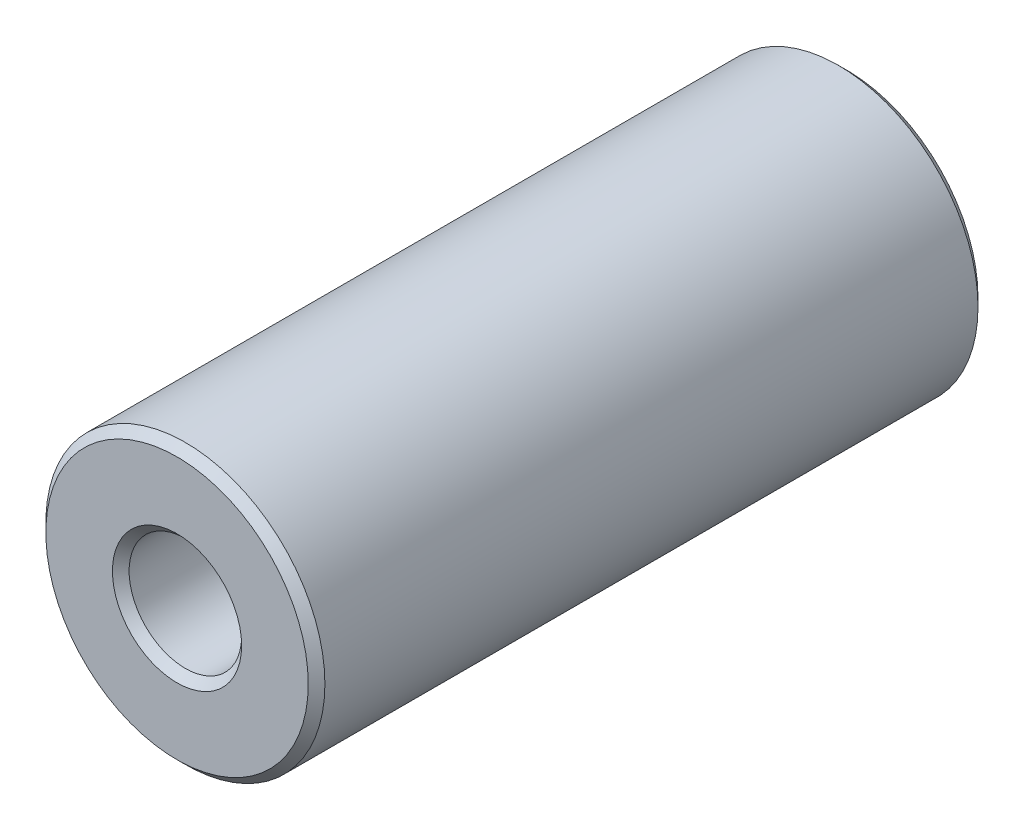
SolidWorks part; units mm, degrees
ref_plane "Front Plane" through (0, 0, 0) normal (0, 0, 1) x (1, 0, 0)
ref_plane "Top Plane" through (0, 0, 0) normal (0, 1, 0) x (1, 0, 0)
ref_plane "Right Plane" through (0, 0, 0) normal (1, 0, 0) x (0, 0, -1)
sketch "Sketch1" plane through (0, 0, 0) normal (0, 0, 1) x (1, 0, 0)
  circle A0 centre (0, 0) radius 7.9375 construction
  circle A1 centre (0, 0) radius 3.2004 construction
  point P4 (0, 7.9375)
  dimension "ID" = 6.4008
  dimension "OD" = 15.875
sketch "Sketch2" plane through (0, 0, 0) normal (1, 0, 0) x (0, 0, -1)
  line L0 (-19.05, 7.9375) -> (19.05, 7.9375) construction
  dimension "Length" = 38.1
sketch "Sketch3" plane through (0, 0, 0) normal (0, 0, 1) x (1, 0, 0)
  circle A0 centre (0, 0) radius 3.2004 construction
  circle A1 centre (0, 0) radius 7.9375 construction
  circle A2 centre (0, 0) radius 3.2004
  circle A3 centre (0, 0) radius 7.9375
extrude "Boss-Extrude1" add sketch "Sketch3" against normal up to vertex (19.05 mm away) and the other way up to vertex (19.05 mm away) up to point (0, 7.9375, -19.05) other way up to point (0, 7.9375, 19.05)
chamfer "Chamfer1" distance 0.4737 angle 45 4 edges at (7.9375, 0, 19.05) (7.9375, 0, -19.05) (3.2004, 0, 19.05) (3.2004, 0, -19.05)
equation "\"D1@Chamfer1\"=(\"OD@Sketch1\"-\"ID@Sketch1\")*0.05"
